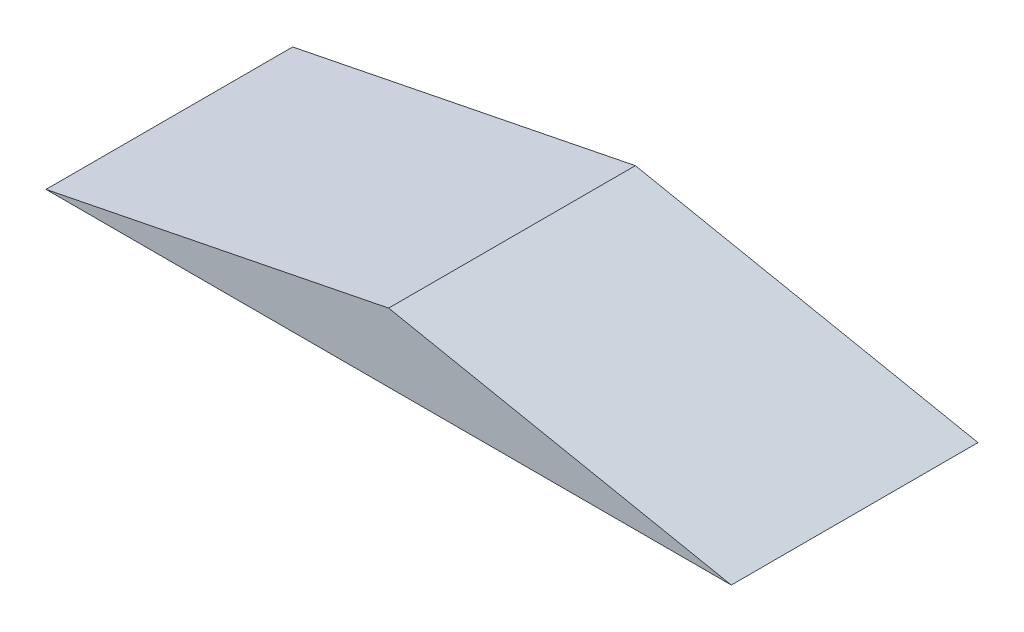
SolidWorks part; units mm, degrees
ref_plane "Front Plane" through (0, 0, 0) normal (0, 0, 1) x (1, 0, 0)
ref_plane "Top Plane" through (0, 0, 0) normal (0, 1, 0) x (1, 0, 0)
ref_plane "Right Plane" through (0, 0, 0) normal (1, 0, 0) x (0, 0, -1)
sketch "Sketch1" plane through (0, 0, 0) normal (0, 0, 1) x (1, 0, 0)
  line L0 (0, 0) -> (5000, 0)
  line L1 (2500, 0) -> (2500, 500) construction
  line L2 (0, 0) -> (2500, 500)
  line L3 (2500, 500) -> (5000, 0)
  dimension "D1" = 5000
  dimension "D2" = 500
extrude "Boss-Extrude1" add sketch "Sketch1" along normal blind 1800
